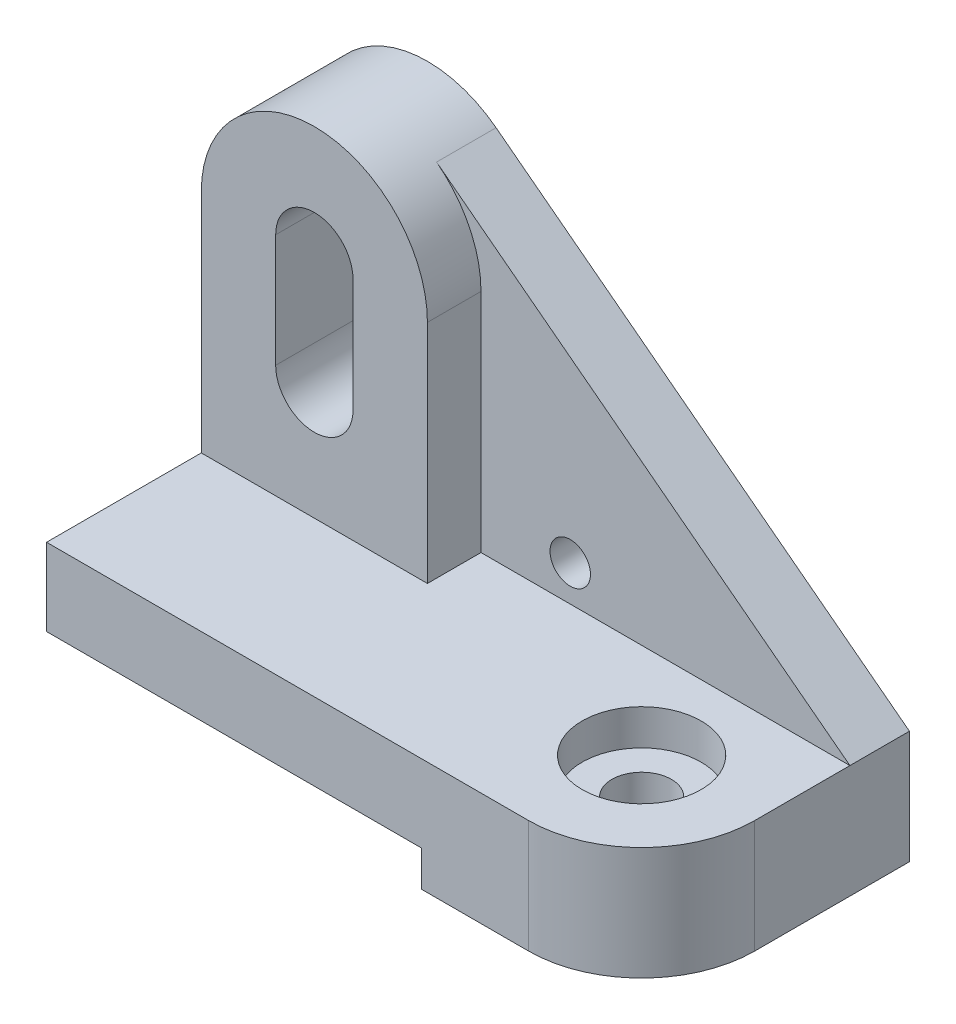
SolidWorks part; units mm, degrees
ref_plane "Front Plane" through (0, 0, 0) normal (0, 0, 1) x (1, 0, 0)
ref_plane "Top Plane" through (0, 0, 0) normal (0, 1, 0) x (1, 0, 0)
ref_plane "Right Plane" through (0, 0, 0) normal (1, 0, 0) x (0, 0, -1)
sketch "Sketch1" plane through (0, 0, 0) normal (0, 0, 1) x (1, 0, 0)
  line L0 (0, 0) -> (0, -13)
  line L1 (0, -13) -> (63, -13)
  line L2 (63, -13) -> (63, -19)
  line L3 (63, -19) -> (100, -19)
  line L4 (100, -19) -> (100, 0)
  line L5 (100, 0) -> (0, 0)
  dimension "D2" = 0
  dimension "D6" = 0
extrude "Boss-Extrude1" add sketch "Sketch1" along normal blind 45
sketch "Sketch2" plane through (0, 0, 0) normal (0, 0, -1) x (-1, 0, 0)
  line L0 (0, 0) -> (0, 38)
  line L2 (0, 0) -> (-100, 0)
  line L4 (-100, 0) -> (-30.5385, 53.0952)
  arc A0 (0, 38) -> (-30.5385, 53.0952) centre (-19, 38) ccw
extrude "Boss-Extrude2" add sketch "Sketch2" against normal blind 10
sketch "Sketch4" plane through (0, 0, 10) normal (0, 0, 1) x (1, 0, 0)
  line L0 (0, 0) -> (0, 38)
  line L1 (0, 0) -> (38, 0)
  line L2 (100, 0) -> (0, 0) construction
  line L3 (38, 0) -> (38, 38)
  arc A0 (38, 38) -> (0, 38) centre (19, 38) ccw
  dimension "D2" = 38
extrude "Boss-Extrude3" add sketch "Sketch4" along normal blind 9
sketch "Sketch5" plane through (0, 0, 19) normal (0, 0, 1) x (1, 0, 0)
  line L0 (19, 38) -> (19, 19) construction
  line L1 (25.5, 38) -> (25.5, 19)
  line L2 (12.5, 38) -> (12.5, 19)
  arc A0 (25.5, 38) -> (12.5, 38) centre (19, 38) ccw
  arc A1 (12.5, 19) -> (25.5, 19) centre (19, 19) ccw
  arc A2 (38, 38) -> (0, 38) centre (19, 38) ccw construction
  point P2 (19, 28.5)
extrude "Cut-Extrude1" cut sketch "Sketch5" against normal through all
fillet "Fillet1" radius 19 1 edges at (100, -9.5, 45)
hole_wizard "Hole1" positions "3DSketch1" profile "Sketch6" legacy end condition through all
sketch3d "3DSketch1"
  point P0 (81, 0, 26)
sketch "Sketch6" plane through (81, 0, 26) normal (1, 0, 0) x (0, 0, 1)
  line L0 (0, 0) -> (0, 19)
  line L1 (0, 19) -> (5, 19)
  line L2 (5, 19) -> (5, 6)
  line L3 (5, 6) -> (10, 6)
  line L4 (10, 6) -> (10, 0)
  line L5 (10, 0) -> (0, 0)
  line L6 (0, 110) -> (0, -10) construction
  dimension "Diameter" = 10
  dimension "Depth" = 19
  dimension "C-Bore Diameter" = 20
  dimension "C-Bore Depth" = 6
hole_wizard "M8 Tapped Hole2" positions "3DSketch2" profile "Sketch9" tap size "M8" standard "AS" end condition through all
sketch3d "3DSketch2"
  point P0 (53, 6, 10)
sketch "Sketch9" plane through (53, 6, 10) normal (1, 0, 0) x (0, -1, 0)
  line L0 (0, 0) -> (0, 10)
  line L1 (0, 10) -> (3.4, 10)
  line L2 (3.4, 10) -> (3.4, 0)
  line L5 (3.4, 0) -> (0, 0)
  line L11 (0, -6.35) -> (0, 107.95) construction
  dimension "Thru Tap Drill Dia." = 6.8
  dimension "Thru Tap Drill Depth" = 10
cosmetic thread "Hole Thread2" parameters "D2"=8
